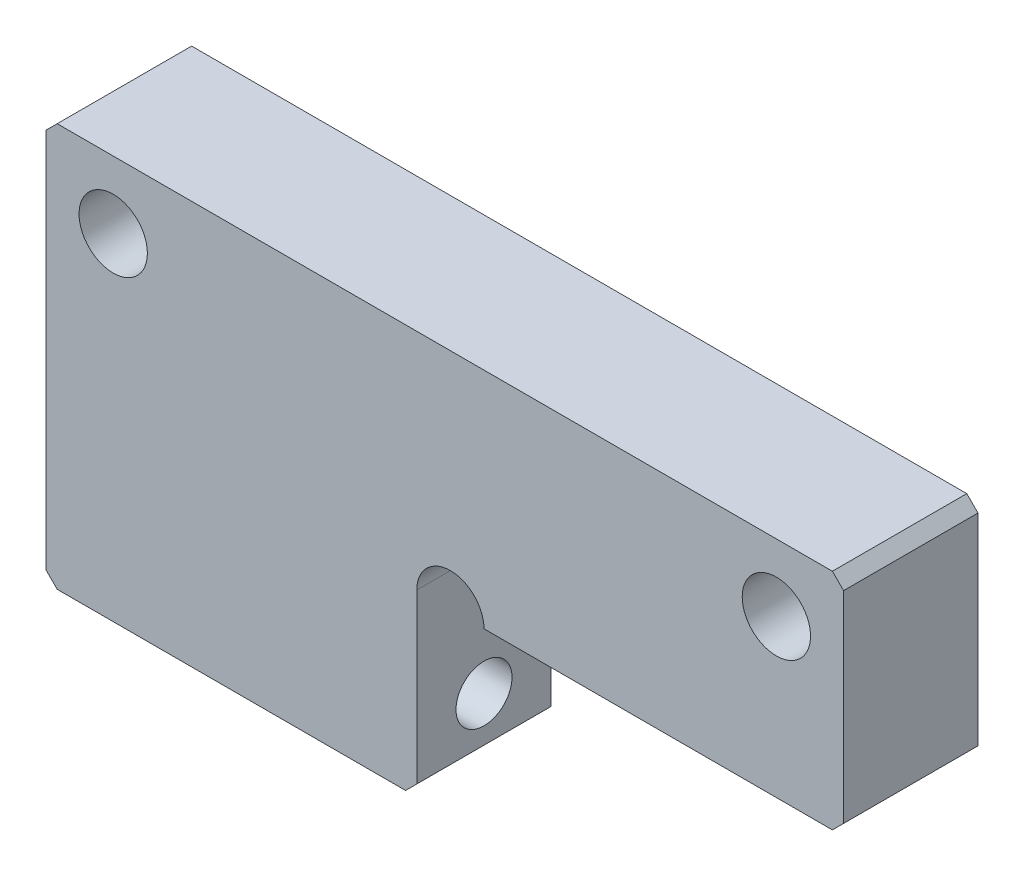
SolidWorks part; units mm, degrees
material "6061 合金"
ref_plane "前视基准面" through (0, 0, 0) normal (0, 0, 1) x (1, 0, 0)
ref_plane "上视基准面" through (0, 0, 0) normal (0, 1, 0) x (1, 0, 0)
ref_plane "右视基准面" through (0, 0, 0) normal (1, 0, 0) x (0, 0, -1)
sketch "草图1" plane through (0, 0, 0) normal (0, 0, 1) x (1, 0, 0)
  line L1 (-17.8, -9) -> (17.8, -9)
  line L2 (-17.8, -9) -> (-17.8, 9)
  line L3 (-17.8, 9) -> (17.8, 9)
  line L4 (17.8, -9) -> (17.8, 9)
  line L5 (0, 9) -> (0, -9) construction
  line L6 (-17.8, 0) -> (17.8, 0) construction
  point P0 (0, 0)
  dimension "D1" = 18
  dimension "D2" = 35.6
extrude "凸台-拉伸1" add sketch "草图1" along normal blind 6
sketch "草图3" plane through (0, 0, 0) normal (0, 0, -1) x (-1, 0, 0)
  line L0 (17.8, -9) -> (-17.8, -9) construction
  line L1 (-1.25, -17) -> (1.25, -17)
  line L2 (-1.25, -17) -> (-1.25, -1)
  line L3 (-1.25, -1) -> (1.25, -1)
  line L4 (1.25, -17) -> (1.25, -1)
  line L5 (0, -1) -> (0, -17) construction
  line L6 (-1.25, -9) -> (1.25, -9) construction
  point P0 (0, -9)
  dimension "D1" = 2.5
  dimension "D2" = 8
extrude "切除-拉伸1" cut sketch "草图3" against normal blind 28
sketch "草图4" plane through (0, 0, 0) normal (0, 0, -1) x (-1, 0, 0)
  line L0 (-17.8, -9) -> (-17.8, 9) construction
  line L1 (-17.8, -1) -> (-1.25, -1)
  line L2 (-17.8, -1) -> (-17.8, -9)
  line L3 (-17.8, -9) -> (-1.25, -9)
  line L4 (-1.25, -1) -> (-1.25, -9)
  line L5 (1.25, -1) -> (-1.25, -1) construction
extrude "切除-拉伸2" cut sketch "草图4" against normal blind 10
sketch "草图5" plane through (-1.25, 0, 0) normal (1, 0, 0) x (0, 0, -1)
  line L0 (-3, -9) -> (-3, -6.5) construction
  line L1 (0, -9) -> (-6, -9) construction
  dimension "D1" = 2.5
hole_wizard "M3 螺纹孔1" positions "草图6" profile "草图7" tap size "M3" standard "GB" end condition through all
sketch "草图6" plane through (-1.25, 0, 0) normal (1, 0, 0) x (0, 0, -1)
  point P0 (-3, -6.5)
sketch "草图7" plane through (-1.25, -6.5, 3) normal (0, 1, 0) x (0, 0, -1)
  line L0 (0, 0) -> (0, 16.55)
  line L1 (0, 16.55) -> (1.25, 16.55)
  line L2 (1.25, 16.55) -> (1.25, 0)
  line L5 (1.25, 0) -> (0, 0)
  line L11 (0, -6.35) -> (0, 107.95) construction
  dimension "通孔螺纹孔钻头直径" = 2.5
  dimension "通孔螺纹孔钻头深度" = 16.55
cosmetic thread "孔螺蚊线1" parameters "D2"=3
sketch "草图8" plane through (0, 0, 6) normal (0, 0, 1) x (1, 0, 0)
  line L0 (-17.8, 6) -> (-14.8, 6) construction
  line L1 (-17.8, 9) -> (-17.8, -9) construction
  line L2 (17.8, 9) -> (-17.8, 9) construction
  line L3 (0, 0) -> (0, 9) construction
  circle A0 centre (-14.8, 6) radius 1.525
  circle A1 centre (14.8, 6) radius 1.525
  dimension "D3" = 3.05
  dimension "D1" = 3
  dimension "D2" = 3
extrude "切除-拉伸3" cut sketch "草图8" against normal blind 22
fillet "圆角1" [suppressed] radius 1
chamfer "倒角1" distance 0.5 angle 45 5 edges at (17.8, -1, 3) (17.8, 9, 3) (-17.8, 9, 3) (-17.8, -9, 3) (-1.25, -9, 3)
sketch "草图9" plane through (0, 0, 6) normal (0, 0, 1) x (1, 0, 0)
  line L0 (-1.25, -1) -> (17.3, -1) construction
  circle A0 centre (0.25, -1) radius 1.5
  dimension "D1" = 3
extrude "切除-拉伸4" cut sketch "草图9" against normal blind 10
